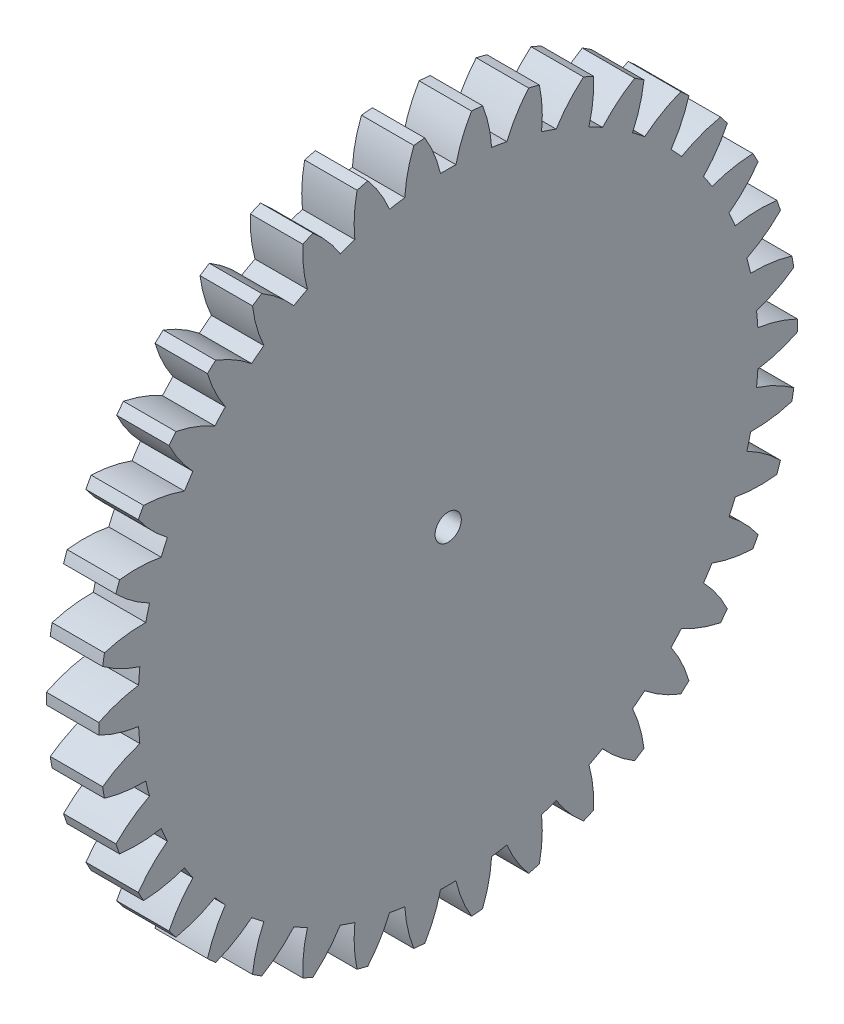
SolidWorks part; units mm, degrees
ref_plane "Plane1" through (0, 0, 0) normal (0, 0, 1) x (1, 0, 0)
ref_plane "Plane2" through (0, 0, 0) normal (0, 1, 0) x (1, 0, 0)
ref_plane "Plane3" through (0, 0, 0) normal (1, 0, 0) x (0, 0, -1)
sketch "HoldingSke" plane through (0, 0, 0) normal (0, 1, 0) x (1, 0, 0)
  line L0 (0, 0) -> (0.197, -0.1539)
  line L1 (-15, 0) -> (100, 0) construction
  line L2 (0, 0) -> (-2.1039, 2.3779)
  line L3 (0, 0) -> (-11.863, 4.5341)
  line L4 (0, 0) -> (6.8053, 5.3169)
  line L5 (0, 0) -> (-46.8476, -17.4728)
  line L6 (0, 0) -> (-9.9476, -6.7116)
  line L7 (-2.1039, 2.3779) -> (8.6586, 51.2059)
  line L8 (-76.2, 54.61) -> (-75.2, 54.61)
  line L9 (-71.009, 38.7566) -> (-53.1078, 45.2721)
  line L10 (-76.2, 71.12) -> (104.1128, 71.12)
  line L11 (0, 0) -> (-12, 0)
  line L12 (-76.2, 101.6) -> (-76.073, 101.6)
  line L13 (24.9733, 27.94) -> (52.9518, 28.4284)
  line L14 (24.9733, 27.94) -> (24.9743, 27.94)
  line L15 (24.9733, 27.94) -> (100.4006, 29.5858)
  line L16 (-63.627, -4) -> (-12.827, -4)
  circle A0 centre (0, 0) radius 3
  circle A1 centre (0, 0) radius 37.5
  circle A2 centre (0, 0) radius 37.5
  circle A3 centre (0, 0) radius 3
  dimension "MHD" = 75
  dimension "Hub_dia" = 75
  dimension "Bore" = 6
  dimension "MBD" = 6
  dimension "Num_teeth" = 38
  dimension "Pitch" = 0.25
  dimension "Overall_len" = 50
  dimension "Show_teeth" = 38
  dimension "Thickness" = 12
  dimension "OAL" = 50.0001
  dimension "T_dim" = 1
  dimension "Ap" = 20
  dimension "H" = 19.05
  dimension "Pitch_radius" = 180.3128
  dimension "Width" = 12
  dimension "Backlash" = 0.127
  dimension "Addendum_fac" = 1
  dimension "Dedendum_fac" = 1.25
  dimension "Clearance_fac" = 0.25
  dimension "Dedendum_add" = 0.001
  dimension "Module" = 4
sketch "BasProSke" plane through (0, 0, 0) normal (0, 1, 0) x (1, 0, 0)
  line L0 (-10, 0) -> (60, 0) construction
  line L1 (0, 0) -> (0, 80)
  line L2 (0, 0) -> (12, 0)
  line L3 (12, 0) -> (12, 80)
  line L4 (12, 80) -> (0, 80)
  dimension "Thickness" = 12
  dimension "Diameter" = 160
revolve "Base-Revolve" add sketch "BasProSke" angle 360 about L0
sketch "TooCutSke" plane through (0, 0, 0) normal (1, 0, 0) x (0, 0, -1)
  line L1 (0, 0) -> (0, 107) construction
  line L2 (0, 0) -> (-3.3629, 75.9256) construction
  line L3 (0, 0) -> (-12.5428, 151.3691) construction
  line L4 (-3.3629, 75.9256) -> (-6.2714, 75.6846) construction
  arc A0 (1.7659, 70.977) -> (-1.7659, 70.977) centre (0, 0) ccw
  arc A1 (5.3554, 79.846) -> (-5.3554, 79.846) centre (0, 0) ccw
  circle A2 centre (0, 0) radius 76 construction
  circle A3 centre (0, 0) radius 71.4166 construction
  arc A4 (-1.7659, 70.977) -> (-5.3554, 79.846) centre (-31.3891, 64.1487) ccw
  arc A5 (5.3554, 79.846) -> (1.7659, 70.977) centre (31.3891, 64.1487) ccw
  dimension "Root_dia" = 141.998
  dimension "Overcut_dia" = 160.0508
  dimension "Pitch_dia" = 152
  dimension "Base_dia" = 142.8333
  dimension "Flank_rad" = 30.4
  dimension "Half_ang" = 4.737
  dimension "Half_CT" = 2.9184
extrude "ToothCut" cut sketch "TooCutSke" along normal through all
fillet "Breaks" [suppressed] radius 0.08
fillet "RootFillets" [suppressed] radius 1.001
pattern_circular "TeethCuts" count 38 every 9.474 about axis through (-10, 0, 0) along (1, 0, 0) of "ToothCut", "RootFillets", "Breaks"
sketch "HubNeaOneSke" plane through (0, 0, 0) normal (-1, 0, 0) x (0, 0, 1)
  circle A0 centre (0, 0) radius 37.5
  dimension "Diameter" = 75
extrude "HubNearOne" [suppressed] add sketch "HubNeaOneSke" along normal blind 38.0001
sketch "HubNeaBotSke" plane through (0, 0, 0) normal (-1, 0, 0) x (0, 0, 1)
  circle A0 centre (0, 0) radius 37.5
  dimension "Diameter" = 75
extrude "HubNearBoth" [suppressed] add sketch "HubNeaBotSke" along normal blind 19
ref_plane "FarPln" through (12, 0, 0) normal (1, 0, 0) x (0, 0, -1)
sketch "HubFarSke" plane through (12, 0, 0) normal (1, 0, 0) x (0, 0, -1)
  circle A0 centre (0, 0) radius 37.5
  dimension "Diameter" = 75
extrude "HubFar" [suppressed] add sketch "HubFarSke" along normal blind 19
sketch "BorSke" plane through (0, 0, 0) normal (1, 0, 0) x (0, 0, -1)
  circle A0 centre (0, 0) radius 3
  dimension "Diameter" = 6
extrude "Bore" cut sketch "BorSke" along normal mid plane 100.0001
sketch "KeySke" plane through (0, 0, 0) normal (1, 0, 0) x (0, 0, -1)
  line L0 (-1, 0) -> (-1, 4)
  line L1 (-1, 4) -> (1, 4)
  line L2 (1, 4) -> (1, 0)
  line L3 (0, 0) -> (0, 34) construction
  line L4 (-1, 0) -> (1, 0)
  dimension "Offset" = 4
  dimension "Width" = 2
extrude "Keyway" [suppressed] cut sketch "KeySke" along normal mid plane 100.0001
pattern_circular "Keyway2" [suppressed] count 2 every 90 about axis through (-10, 0, 0) along (1, 0, 0)
equation "' \"Module@HoldingSke\" = 6.35"
equation "' \"Num_teeth@HoldingSke\" = 12"
equation "' \"Ap@HoldingSke\" =  20"
equation "' \"Ap@HoldingSke\" = 20"
equation "' \"Width@HoldingSke\" = 0.5 * 25.4"
equation "' \"Hub_dia@HoldingSke\"= 1 * 25.4"
equation "' \"Hub_dia@HoldingSke\" = 1 * 25.4"
equation "' \"Overall_len@HoldingSke\" = 1.0 * 25.4"
equation "' \"Bore@HoldingSke\" = 0.75 * 25.4"
equation "' \"T_dim@HoldingSke\" = 0.1 * 25.4"
equation "' \"Width@KeySke\" = 0.25 * 25.4"
equation "' \"Show_teeth@HoldingSke\" = 13"
equation "' \"Backlash@HoldingSke\" = 0.009 * 25.4"
equation "' \"Addendum_fac@HoldingSke\" = 1.0"
equation "' \"Dedendum_fac@HoldingSke\" = 1.25"
equation "' \"Dedendum_add@HoldingSke\" = 0.00005 * 25.4"
equation "' \"Clearance_fac@HoldingSke\" = 0.25"
equation "\"Pitch@HoldingSke\" = 1 / \"Module@HoldingSke\""
equation "\"Overcut_dia@TooCutSke\" = (\"Num_teeth@HoldingSke\" + 2 * \"Addendum_fac@HoldingSke\") / \"Pitch@HoldingSke\" + 0.002 * 25.4"
equation "\"Pitch_dia@TooCutSke\" = \"Num_teeth@HoldingSke\" / \"Pitch@HoldingSke\""
equation "\"Base_dia@TooCutSke\" = \"Num_teeth@HoldingSke\" / \"Pitch@HoldingSke\" * cos((\"Ap@HoldingSke\"  * 3.14159265 / 180))"
equation "\"Root_dia@TooCutSke\" = (\"Num_teeth@HoldingSke\" + 2) / \"Pitch@HoldingSke\" - 2 * (\"Addendum_fac@HoldingSke\" + \"Dedendum_fac@HoldingSke\") / \"Pitch@HoldingSke\" - \"Dedendum_add@HoldingSke\" * 2"
equation "\"Half_ang@TooCutSke\" = 180 / \"Num_teeth@HoldingSke\""
equation "\"Half_CT@TooCutSke\" = \"Num_teeth@HoldingSke\" / \"Pitch@HoldingSke\" * sin((3.14159265 / 2 / \"Num_teeth@HoldingSke\")) / 2 - 7 * \"Backlash@HoldingSke\" / 4"
equation "\"Flank_rad@TooCutSke\" = \"Num_teeth@HoldingSke\" / \"Pitch@HoldingSke\" / 5"
equation "\"Radius@RootFillets\" = \"Clearance_fac@HoldingSke\" / \"Pitch@HoldingSke\" + \"Dedendum_add@HoldingSke\""
equation "\"Break_rad@Breaks\" = 0.02 / \"Pitch@HoldingSke\""
equation "\"Thickness@HoldingSke\" = \"Width@HoldingSke\""
equation "\"OAL@HoldingSke\" = \"Thickness@HoldingSke\""
equation "\"MHD@HoldingSke\" = (\"Num_teeth@HoldingSke\" + 2) / \"Pitch@HoldingSke\" - 2 * (\"Addendum_fac@HoldingSke\" + \"Dedendum_fac@HoldingSke\")  / \"Pitch@HoldingSke\" - \"Dedendum_add@HoldingSke\" * 2"
equation "\"MBD@HoldingSke\" = (\"Num_teeth@HoldingSke\" + 2) / \"Pitch@HoldingSke\" - 2 * (\"Addendum_fac@HoldingSke\" + \"Dedendum_fac@HoldingSke\")  / \"Pitch@HoldingSke\" - \"Dedendum_add@HoldingSke\" * 2 - 0.002 * 25.4"
equation "\"MHD@HoldingSke\" = ((sgn( \"MHD@HoldingSke\" - \"Hub_dia@HoldingSke\" )-1)*( \"MHD@HoldingSke\" - \"Hub_dia@HoldingSke\" ))/-2+ \"Hub_dia@HoldingSke\""
equation "\"MBD@HoldingSke\" = ((sgn( \"MBD@HoldingSke\" - \"Bore@HoldingSke\" )-1)*( \"MBD@HoldingSke\" - \"Bore@HoldingSke\" ))/-2+ \"Bore@HoldingSke\""
equation "\"OAL@HoldingSke\" = ((sgn( \"OAL@HoldingSke\" - \"Overall_len@HoldingSke\" )+1)*( \"OAL@HoldingSke\" - \"Overall_len@HoldingSke\" ))/2 + \"Overall_len@HoldingSke\" + 0.000002 * 25.4"
equation "\"Num_teeth@TeethCuts\" = int( \"Show_teeth@HoldingSke\" ) + 1"
equation "\"Num_teeth@TeethCuts\" = ((sgn( \"Num_teeth@TeethCuts\" - \"Num_teeth@HoldingSke\" )-1)*( \"Num_teeth@TeethCuts\" - \"Num_teeth@HoldingSke\" ))/-2+ \"Num_teeth@HoldingSke\""
equation "\"Num_teeth@TeethCuts\" = ((sgn( \"Num_teeth@TeethCuts\" - 2.0)+1)*( \"Num_teeth@TeethCuts\" - 2.0))/2 +2.0"
equation "\"Angle@TeethCuts\" = 360.0 / \"Num_teeth@HoldingSke\""
equation "\"Diameter@BasProSke\" = (\"Num_teeth@HoldingSke\" + 2 * \"Addendum_fac@HoldingSke\") / \"Pitch@HoldingSke\""
equation "\"Thickness@BasProSke\"  = \"Thickness@HoldingSke\""
equation "' \"Fillet_rad@BasProSke\" =  \"Thickness@HoldingSke\" * 0.05"
equation "' \"Fillet_rad@BasProSke\" = \"Thickness@HoldingSke\" * 0.05"
equation "\"MHD@HoldingSke\" = ((sgn( \"MHD@HoldingSke\" - \"Root_dia@TooCutSke\" )-1)*( \"MHD@HoldingSke\" - \"Root_dia@TooCutSke\" ))/-2+ \"Root_dia@TooCutSke\""
equation "\"Diameter@HubNeaOneSke\" = \"MHD@HoldingSke\""
equation "\"Length@HubNearOne\" = \"OAL@HoldingSke\" - \"Thickness@BasProSke\""
equation "\"Diameter@HubNeaBotSke\" = \"MHD@HoldingSke\""
equation "\"Length@HubNearBoth\" = ( \"OAL@HoldingSke\" - \"Thickness@BasProSke\" ) / 2.0"
equation "\"Thickness@FarPln\" = \"Thickness@BasProSke\""
equation "\"Diameter@HubFarSke\" = \"MHD@HoldingSke\""
equation "\"Length@HubFar\" = ( \"OAL@HoldingSke\" - \"Thickness@BasProSke\" ) / 2.0"
equation "\"Diameter@BorSke\" = \"MBD@HoldingSke\""
equation "\"D1@Bore\" = \"OAL@HoldingSke\" * 2.0"
equation "\"D1@Keyway\" = \"OAL@HoldingSke\" * 2.0"
equation "\"Offset@KeySke\" = \"T_dim@HoldingSke\" + \"MBD@HoldingSke\" / 2.0"
